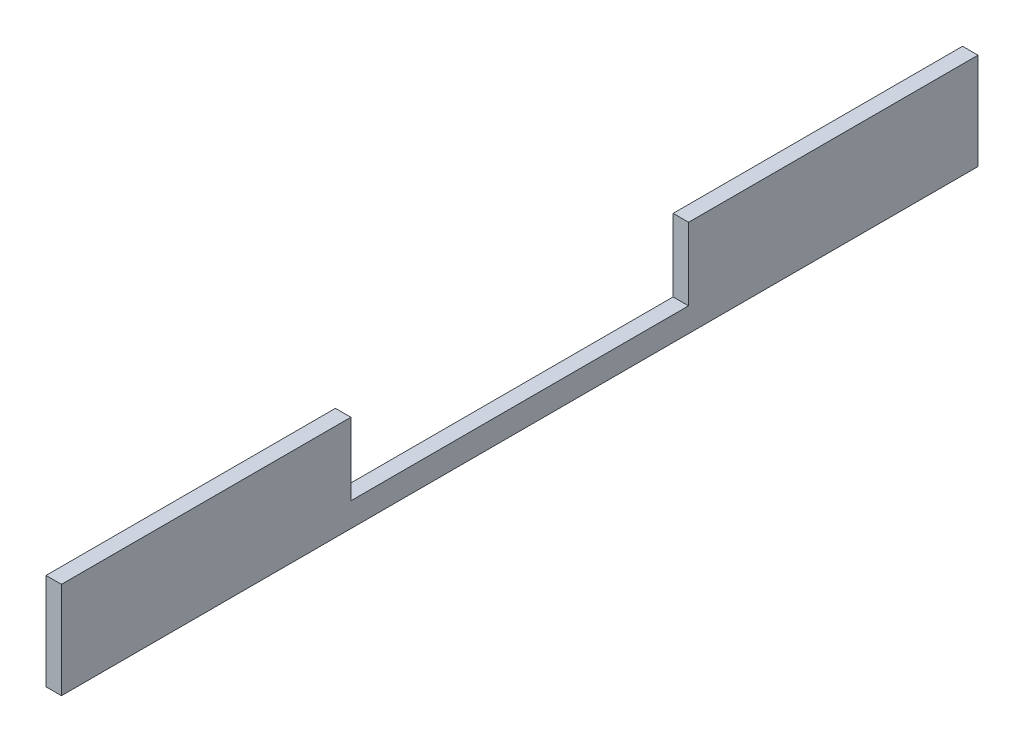
SolidWorks part; units mm, degrees
material "Balsa"
ref_plane "Front Plane" through (0, 0, 0) normal (0, 0, 1) x (1, 0, 0)
ref_plane "Top Plane" through (0, 0, 0) normal (0, 1, 0) x (1, 0, 0)
ref_plane "Right Plane" through (0, 0, 0) normal (1, 0, 0) x (0, 0, -1)
sketch "Sketch1" plane through (0, 0, 0) normal (1, 0, 0) x (0, 0, -1)
  line L1 (0, 0) -> (190, 0)
  line L2 (0, 0) -> (0, 20)
  line L3 (0, 20) -> (190, 20)
  line L4 (190, 0) -> (190, 20)
  dimension "D1" = 20
  dimension "D2" = 190
extrude "Boss-Extrude1" add sketch "Sketch1" along normal blind 3.2
sketch "Sketch2" plane through (0, 0, 0) normal (-1, 0, 0) x (0, 0, 1)
  line L0 (-95, 20) -> (-95, 5)
  line L3 (-190, 20) -> (0, 20) construction
  line L4 (-130, 20) -> (-130, 5)
  line L5 (-60, 20) -> (-60, 5)
  line L6 (-130, 5) -> (-60, 5)
  line L7 (-130, 20) -> (-60, 20)
  line M3 (0, 20) -> (-190, 20)
  dimension "D1" = 15
  dimension "D2" = 35
  dimension "D3" = 35
extrude "Cut-Extrude1" cut sketch "Sketch2" against normal blind 10 contours L4 L6 L0 M3 | L0 L6 L5 M3
